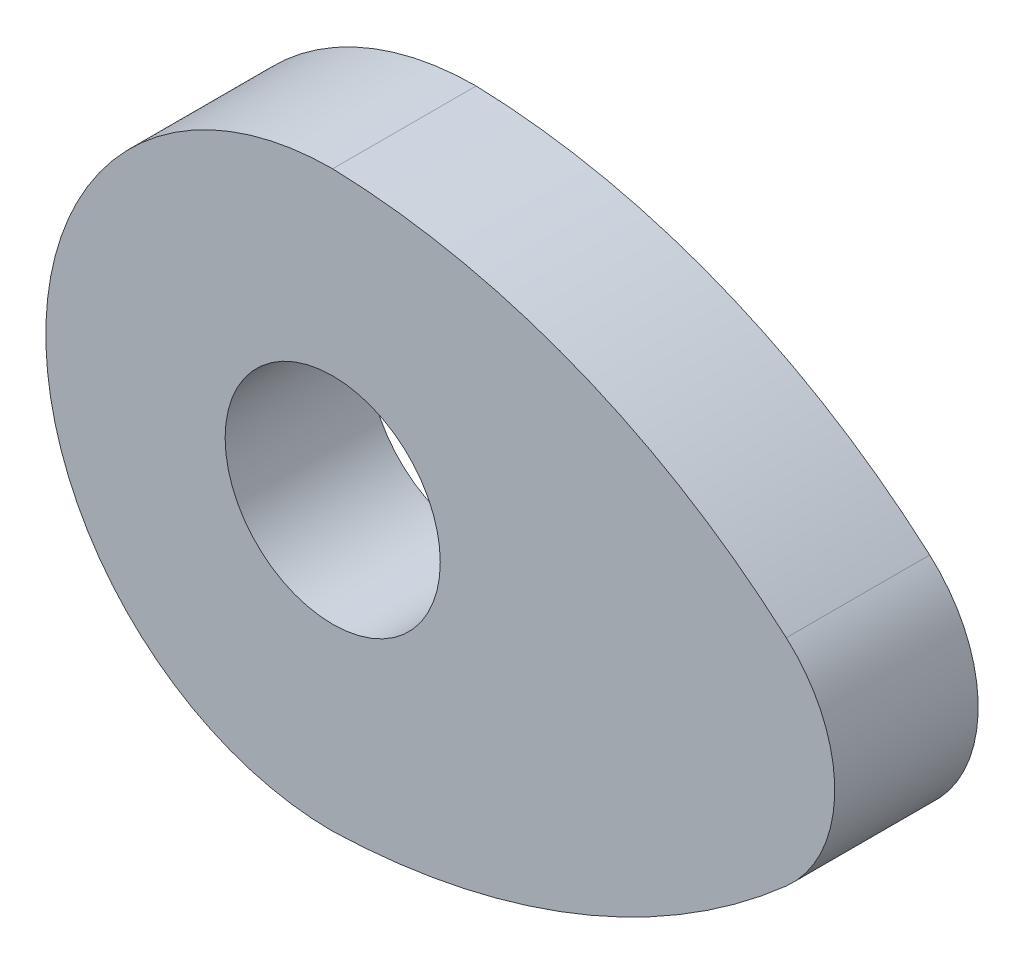
SolidWorks part; units mm, degrees
ref_plane "Front Plane" through (0, 0, 0) normal (0, 0, 1) x (1, 0, 0)
ref_plane "Top Plane" through (0, 0, 0) normal (0, 1, 0) x (1, 0, 0)
ref_plane "Right Plane" through (0, 0, 0) normal (1, 0, 0) x (0, 0, -1)
sketch "Sketch1" plane through (0, 0, 0) normal (0, 0, 1) x (1, 0, 0)
  arc A0 (1.9732, 19.9024) -> (1.9732, -19.9024) centre (0, 0) ccw
  arc A1 (31.6206, -7.4945) -> (31.6206, 7.4945) centre (25, 0) ccw
  arc A2 (0, 20) -> (31.6206, 7.4945) centre (-1.4824, -29.978) cw
  arc A3 (0, -20) -> (31.6206, -7.4945) centre (-1.4824, 29.978) ccw
  circle A4 centre (0, 0) radius 7.5
  dimension "D1" = 40
  dimension "D2" = 20
  dimension "D4" = 50
  dimension "D5" = 50
  dimension "D6" = 15
  dimension "D3" = 25
extrude "Boss-Extrude1" add sketch "Sketch1" along normal mid plane 10 contours A0 A3 A1 A2 A4
